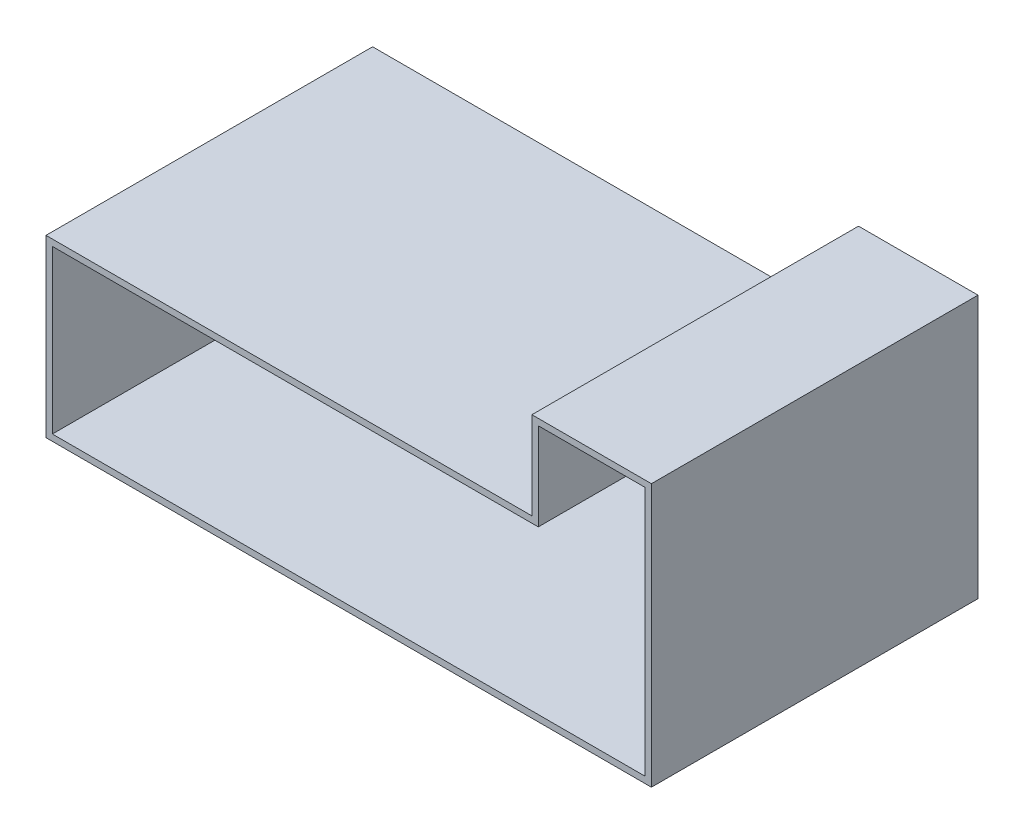
SolidWorks part; units mm, degrees
ref_plane "Front Plane" through (0, 0, 0) normal (0, 0, 1) x (1, 0, 0)
ref_plane "Top Plane" through (0, 0, 0) normal (0, 1, 0) x (1, 0, 0)
ref_plane "Right Plane" through (0, 0, 0) normal (1, 0, 0) x (0, 0, -1)
sketch "Sketch1" plane through (0, 0, 0) normal (0, 1, 0) x (1, 0, 0)
  line L1 (-515.2212, 96.1504) -> (94.7788, 96.1504)
  line L2 (-515.2212, 96.1504) -> (-515.2212, -313.8496)
  line L3 (-515.2212, -313.8496) -> (94.7788, -313.8496)
  line L4 (94.7788, 96.1504) -> (94.7788, -313.8496)
  dimension "D1" = 410
  dimension "D2" = 610
extrude "Boss-Extrude1" add sketch "Sketch1" along normal blind 220
sketch "Sketch2" plane through (94.7788, 0, 0) normal (1, 0, 0) x (0, 0, -1)
  line L0 (-313.8496, 220) -> (-313.8496, 0) construction
  line L2 (-313.8496, 330) -> (96.1504, 330)
  line L3 (-313.8496, 330) -> (-313.8496, 0)
  line L4 (-313.8496, 0) -> (96.1504, 0)
  line L5 (96.1504, 330) -> (96.1504, 0)
  dimension "D1" = 330
extrude "Boss-Extrude2" add sketch "Sketch2" along normal blind 150
sketch "Sketch3" plane through (0, 0, 313.8496) normal (0, 0, 1) x (1, 0, 0)
  line L1 (-507.2212, 212) -> (94.7788, 212)
  line L2 (-507.2212, 212) -> (-507.2212, 8)
  line L3 (-507.2212, 8) -> (94.7788, 8)
  line L4 (94.7788, 212) -> (94.7788, 8)
  line L6 (-515.2212, 220) -> (-515.2212, 0) construction
  line L7 (94.7788, 330) -> (94.7788, 220) construction
  point P4 (-507.2212, 110)
  point P7 (-515.2212, 110)
  dimension "D1" = 602
  dimension "D2" = 204
extrude "Cut-Extrude1" cut sketch "Sketch3" against normal blind 402
sketch "Sketch5" plane through (0, 0, 313.8496) normal (0, 0, 1) x (1, 0, 0)
  line L1 (94.7788, 212) -> (236.7788, 212)
  line L2 (94.7788, 212) -> (94.7788, 8)
  line L3 (94.7788, 8) -> (236.7788, 8)
  line L4 (236.7788, 212) -> (236.7788, 8)
  dimension "D1" = 142
extrude "Cut-Extrude2" cut sketch "Sketch5" against normal blind 402
sketch "Sketch6" plane through (0, 0, 313.8496) normal (0, 0, 1) x (1, 0, 0)
  line L0 (244.7788, 330) -> (94.7788, 330) construction
  line L1 (102.7788, 322) -> (236.7788, 322)
  line L2 (102.7788, 322) -> (102.7788, 212)
  line L3 (102.7788, 212) -> (236.7788, 212)
  line L4 (236.7788, 322) -> (236.7788, 212)
  dimension "D1" = 134
  dimension "D2" = 8
extrude "Cut-Extrude3" cut sketch "Sketch6" against normal blind 402
